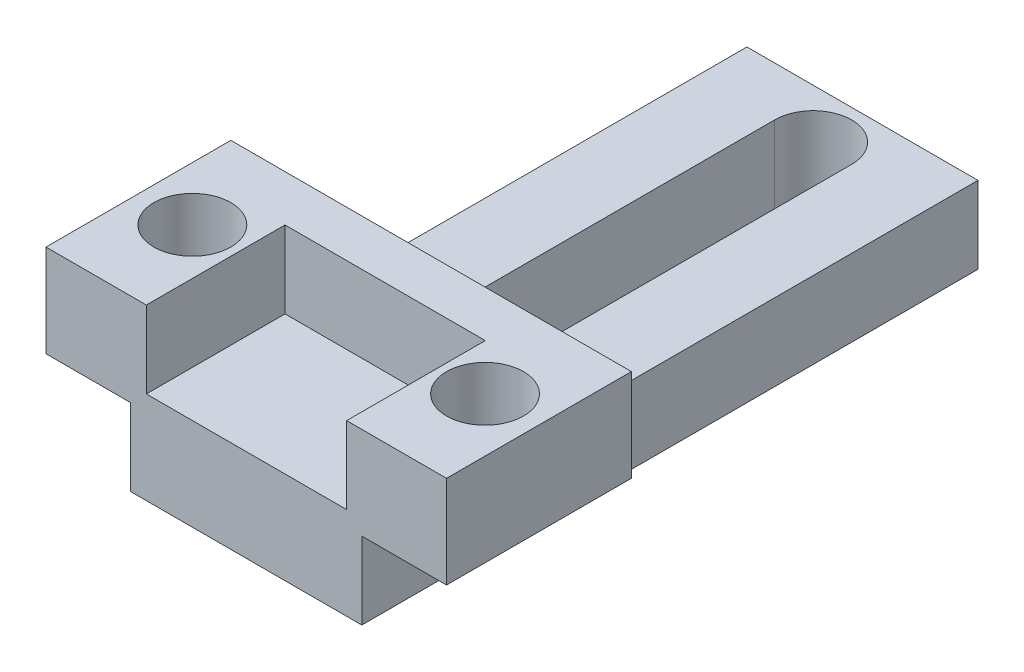
SolidWorks part; units mm, degrees
ref_plane "前基準面" through (0, 0, 0) normal (0, 0, 1) x (1, 0, 0)
ref_plane "上基準面" through (0, 0, 0) normal (0, 1, 0) x (1, 0, 0)
ref_plane "右基準面" through (0, 0, 0) normal (1, 0, 0) x (0, 0, -1)
sketch "草圖1" plane through (0, 0, 0) normal (0, 1, 0) x (1, 0, 0)
  line L0 (0, 16.7993) -> (0, -11.7007) construction
  line L1 (7.5, 20) -> (-7.5, 20)
  line L2 (7.5, 20) -> (7.5, -20)
  line L3 (7.5, -20) -> (-7.5, -20)
  line L4 (-7.5, 20) -> (-7.5, -20)
  line L5 (0, -20) -> (0, 20) construction
  line L6 (7.5, 0) -> (-7.5, 0) construction
  line L7 (2.5, 16.7993) -> (2.5, -11.7007)
  line L8 (-2.5, 16.7993) -> (-2.5, -11.7007)
  arc A0 (2.5, 16.7993) -> (-2.5, 16.7993) centre (0, 16.7993) ccw
  arc A1 (-2.5, -11.7007) -> (2.5, -11.7007) centre (0, -11.7007) ccw
  point P0 (0, 0)
  point P6 (0, 2.5493)
  point P11 (0, -9.2007)
  dimension "D4" = 26
  dimension "D1" = 40
  dimension "D2" = 15
  dimension "D3" = 5
extrude "填料-伸長1" add sketch "草圖1" along normal blind 5
sketch "草圖2" plane through (0, 5, 0) normal (0, 1, 0) x (1, 0, 0)
  line L0 (0, 21.9255) -> (0, -23.6496) construction
  line L1 (-13, -14) -> (13, -14) construction
  line L2 (13, -20) -> (-13, -20)
  line L3 (13, -20) -> (13, -8)
  line L4 (13, -8) -> (-13, -8)
  line L5 (-13, -20) -> (-13, -8)
  line L6 (0, -8) -> (0, -20) construction
  line L7 (13, -14) -> (-13, -14) construction
  line L8 (-7.5, -20) -> (7.5, -20) construction
  circle A0 centre (-9.5, -14) radius 2.5
  circle A1 centre (9.5, -14) radius 2.5
  point P3 (0, -14)
  dimension "D3" = 5
  dimension "D1" = 12
  dimension "D2" = 26
  dimension "D4" = 19
extrude "填料-伸長2" add sketch "草圖2" along normal blind 6
sketch "草圖3" plane through (0, 11, 0) normal (0, 1, 0) x (1, 0, 0)
  line L0 (0, -20) -> (0, -8) construction
  line L1 (-13, -20) -> (13, -20) construction
  line L2 (13, -8) -> (-13, -8) construction
  line L4 (-6.4845, -20) -> (6.5155, -20)
  line L5 (-6.4845, -20) -> (-6.4845, -11)
  line L6 (-6.4845, -11) -> (6.5155, -11)
  line L7 (6.5155, -20) -> (6.5155, -11)
  dimension "D1" = 13
  dimension "D2" = 9
extrude "除料-伸長1" cut sketch "草圖3" against normal blind 5
